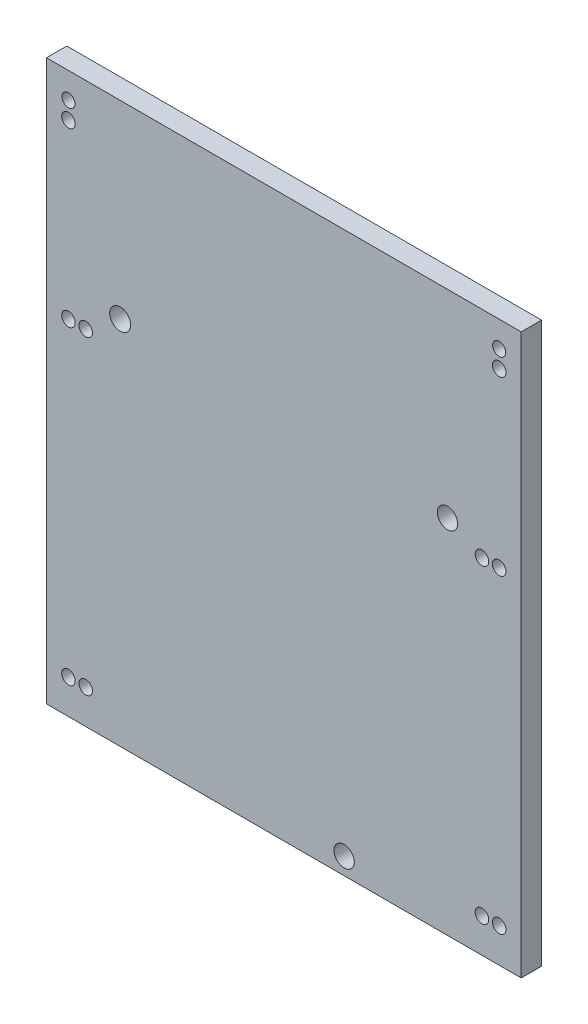
SolidWorks part; units mm, degrees
ref_plane "Plan de face" through (0, 0, 0) normal (0, 0, 1) x (1, 0, 0)
ref_plane "Plan de dessus" through (0, 0, 0) normal (0, 1, 0) x (1, 0, 0)
ref_plane "Plan de droite" through (0, 0, 0) normal (1, 0, 0) x (0, 0, -1)
sketch "Esquisse1" plane through (0, 0, 0) normal (0, 0, 1) x (1, 0, 0)
  line L1 (0, 0) -> (70, 0)
  line L2 (0, 0) -> (0, 82.5)
  line L3 (0, 82.5) -> (70, 82.5)
  line L4 (70, 0) -> (70, 82.5)
  circle A2 centre (43.89, 2.5) radius 1.5
  circle A3 centre (10.87, 54.57) radius 1.5489
  circle A4 centre (59.13, 53.3) radius 1.5
  circle A5 centre (3.25, 78.7) radius 0.9656
  circle A6 centre (3.25, 76.16) radius 1
  circle A9 centre (66.75, 78.7) radius 0.9656
  circle A10 centre (66.75, 76.16) radius 1
  circle A11 centre (3.25, 5.04) radius 1
  circle A12 centre (5.79, 5.04) radius 1
  circle A13 centre (66.75, 5.04) radius 1
  circle A14 centre (64.21, 5.04) radius 1
  circle A15 centre (3.25, 50.76) radius 1
  circle A16 centre (5.79, 50.76) radius 1
  circle A17 centre (66.75, 50.76) radius 1
  circle A18 centre (64.21, 50.76) radius 1
  point P31 (0, 0)
  point P36 (0, 0)
  dimension "D12" = 2.54
  dimension "D4" = 3
  dimension "D7" = 3
  dimension "D14" = 2
  dimension "D18" = 5.04
  dimension "D16" = 2.54
  dimension "D1" = 70
  dimension "D2" = 43.89
  dimension "D3" = 2.5
  dimension "D5" = 54.57
  dimension "D6" = 10.87
  dimension "D8" = 53.3
  dimension "D9" = 48.26
  dimension "D10" = 3.25
  dimension "D11" = 3.8
  dimension "D13" = 82.5
  dimension "D17" = 3.25
  dimension "D19" = 2
  dimension "D21" = 3.25
  dimension "D22" = 5.04
  dimension "D23" = 2
  dimension "D15" = 2
  dimension "D20" = 2
  dimension "D24" = 2
extrude "Boss.-Extru.1" add sketch "Esquisse1" along normal blind 3
